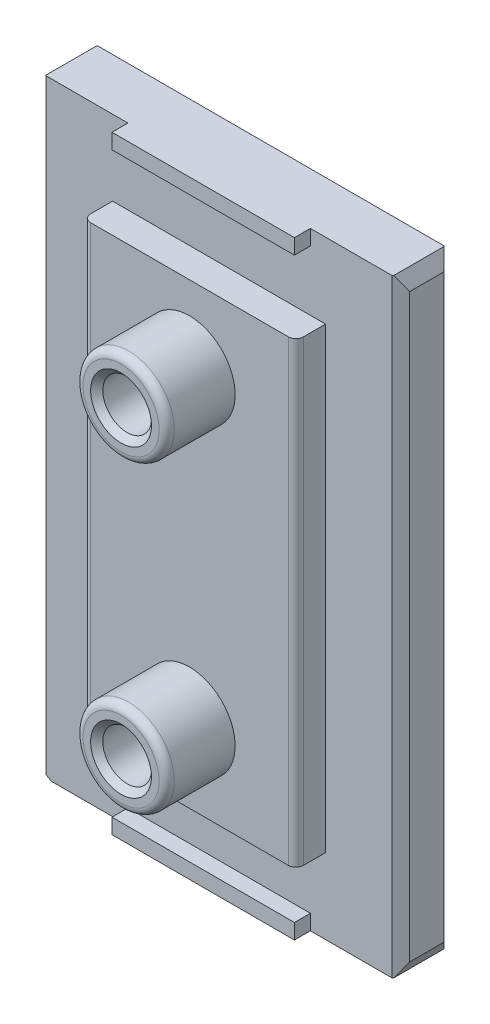
SolidWorks part; units mm, degrees
ref_plane "Plan de face" through (0, 0, 0) normal (0, 0, 1) x (1, 0, 0)
ref_plane "Plan de dessus" through (0, 0, 0) normal (0, 1, 0) x (1, 0, 0)
ref_plane "Plan de droite" through (0, 0, 0) normal (1, 0, 0) x (0, 0, -1)
ref_plane "Plan1" through (0, 0, 7.55) normal (0, 0, 1) x (1, 0, 0)
sketch "Esquisse1" plane through (0, 0, 7.55) normal (0, 0, 1) x (1, 0, 0)
  line L0 (11.95, 20) -> (-11.95, 20)
  line L1 (-11.95, 20) -> (-11.95, -20)
  line L2 (-11.95, -20) -> (11.95, -20)
  line L3 (11.95, -20) -> (11.95, 20)
extrude "Boss.-Extru.1" add sketch "Esquisse1" against normal blind 3.4
ref_plane "Plan2" through (0, 15, 0) normal (0, 1, 0) x (1, 0, 0)
sketch "Esquisse2" plane through (0, 15, 0) normal (0, 1, 0) x (1, 0, 0)
  line L0 (6.995, -7.4) -> (6.995, -7.55)
  line L1 (6.995, -7.55) -> (7, -7.55)
  line L2 (7, -7.55) -> (7, -7.3107)
  arc A0 (7, -7.3107) -> (6.995, -7.4) centre (7.795, -7.4) ccw
extrude "Enlèv. mat.-Extru.1" cut sketch "Esquisse2" against normal blind 30
sketch "Esquisse3" plane through (0, 0, 7.55) normal (0, 0, 1) x (1, 0, 0)
  line L0 (-7.005, 15.05) -> (6.995, 15.05)
  line L1 (6.995, 15.05) -> (6.995, -15.05)
  line L2 (6.995, -15.05) -> (-7.005, -15.05)
  line L3 (-7.005, -15.05) -> (-7.005, 15.05)
extrude "Boss.-Extru.2" add sketch "Esquisse3" along normal blind 1.95
sketch "Esquisse4" plane through (0, 0, 4.15) normal (0, 0, -1) x (-1, 0, 0)
  line L0 (5.2, 15) -> (-5.2, 15)
  line L1 (-5.2, 15) -> (-5.2, -15)
  line L2 (-5.2, -15) -> (5.2, -15)
  line L3 (5.2, -15) -> (5.2, 15)
extrude "Enlèv. mat.-Extru.2" cut sketch "Esquisse4" against normal blind 1.55
ref_plane "Plan3" through (0, 0, 4.15) normal (0, 0, -1) x (-1, 0, 0)
ref_plane "Plan4" through (0, 0, 5.1) normal (0, 0, 1) x (1, 0, 0)
sketch "Esquisse6" plane through (0, 0, 5.1) normal (0, 0, 1) x (1, 0, 0)
  line L0 (5.2, -15) -> (-5.2, -15)
  line L1 (-5.2, -15) -> (-5.2, -16.75)
  line L2 (-5.2, -16.75) -> (5.2, -16.75)
  line L3 (5.2, -16.75) -> (5.2, -15)
extrude "Enlèv. mat.-Extru.3" cut sketch "Esquisse6" against normal up to surface up to plane "Plan3"
sketch "Esquisse8" plane through (0, 0, 5.1) normal (0, 0, 1) x (1, 0, 0)
  line L0 (-5.2, 15) -> (5.2, 15)
  line L1 (5.2, 15) -> (5.2, 16.75)
  line L2 (5.2, 16.75) -> (-5.2, 16.75)
  line L3 (-5.2, 16.75) -> (-5.2, 15)
extrude "Enlèv. mat.-Extru.4" cut sketch "Esquisse8" against normal up to surface up to plane "Plan3"
sketch "Esquisse9" plane through (5.2, 0, 0) normal (-1, 0, 0) x (0, 0, 1)
  line L0 (5.7, -15) -> (5.7, 15)
  line L1 (5.7, 15) -> (5.1, 15)
  line L2 (5.1, 15) -> (5.1, -15)
  line L3 (5.1, -15) -> (5.7, -15)
extrude "Enlèv. mat.-Extru.5" cut sketch "Esquisse9" against normal blind 1.8
sketch "Esquisse10" plane through (-5.2, 0, 0) normal (1, 0, 0) x (0, 0, -1)
  line L0 (-5.7, 15) -> (-5.7, -15)
  line L1 (-5.7, -15) -> (-5.1, -15)
  line L2 (-5.1, -15) -> (-5.1, 15)
  line L3 (-5.1, 15) -> (-5.7, 15)
extrude "Enlèv. mat.-Extru.6" cut sketch "Esquisse10" against normal blind 1.8
sketch "Esquisse11" plane through (0, 0, 7.55) normal (0, 0, 1) x (1, 0, 0)
  line L0 (-6, -20) -> (-6, -19)
  line L1 (-6, -19) -> (6, -19)
  line L2 (6, -19) -> (6, -20)
  line L3 (6, -20) -> (-6, -20)
extrude "Boss.-Extru.3" add sketch "Esquisse11" along normal blind 1.05
sketch "Esquisse12" plane through (0, 0, 7.55) normal (0, 0, 1) x (1, 0, 0)
  line L0 (-6, 19) -> (-6, 20)
  line L1 (-6, 20) -> (6, 20)
  line L2 (6, 20) -> (6, 19)
  line L3 (6, 19) -> (-6, 19)
extrude "Boss.-Extru.4" add sketch "Esquisse12" along normal blind 1.05
ref_plane "Plan5" through (0, 10, 0) normal (0, -1, 0) x (1, 0, 0)
sketch "Esquisse13" plane through (0, 10, 0) normal (0, -1, 0) x (1, 0, 0)
  line L0 (3, 14) -> (0, 14)
  line L1 (0, 14) -> (0, 9.5)
  line L2 (0, 9.5) -> (3, 9.5)
  line L3 (3, 9.5) -> (3, 14)
  line L4 (0, 14) -> (0, 9.5) construction
revolve "Révolution1" add sketch "Esquisse13" angle 360 about L4
ref_plane "Plan6" through (0, -10, 0) normal (0, -1, 0) x (1, 0, 0)
sketch "Esquisse14" plane through (0, -10, 0) normal (0, -1, 0) x (1, 0, 0)
  line L0 (3, 14) -> (0, 14)
  line L1 (0, 14) -> (0, 9.5)
  line L2 (0, 9.5) -> (3, 9.5)
  line L3 (3, 9.5) -> (3, 14)
  line L4 (0, 14) -> (0, 9.5) construction
revolve "Révolution2" add sketch "Esquisse14" angle 360 about L4
hole_wizard "Chambrage pour vis à tête hexagonale M31" positions "Esquisse16" profile "Esquisse15" counterbore size "M3" standard "Ansi Metric"
sketch "Esquisse16" plane through (0, 0, 5.7) normal (0, 0, -1) x (-1, 0, 0)
  point P0 (0, -10)
  point P1 (0, 10)
sketch "Esquisse15" plane through (0, -10, 5.7) normal (1, 0, 0) x (0, 1, 0)
  line L0 (0, 0) -> (0, 8.3)
  line L1 (0, 8.3) -> (1.6, 8.3)
  line L3 (1.6, 8.3) -> (1.6, 2.3)
  line L4 (1.6, 2.3) -> (4, 2.3)
  line L5 (4, 2.3) -> (4, 0)
  line L7 (4, 0) -> (0, 0)
  line L11 (0, -6.35) -> (0, 107.95) construction
  dimension "Diamètre du perçage jusqu'au prochain" = 3.2
  dimension "Profondeur du perçage jusqu'au prochain" = 8.3
  dimension "Diamètre du chambrage" = 8
  dimension "Profondeur du chambrage" = 2.3
chamfer "Chanfrein1" distance 0.9133 angle 29.985 1 edges at (11.95, 20, 5.85)
chamfer "Chanfrein2" distance 0.527 angle 60.015 3 edges at (-11.95, -20, 5.85) (-11.95, 20, 5.85) (11.95, -20, 5.85)
chamfer "Chanfrein3" distance 0.577 angle 45 4 edges at (-11.95, -0.1932, 4.15) (-11.95, -0.1932, 7.55) (11.95, 0, 4.15) (11.95, 0, 7.55)
chamfer "Chanfrein4" distance 0.4 angle 45 4 edges at (-1.6, -10, 8) (-1.6, 10, 14) (-1.6, 10, 8) (-1.6, -10, 14)
fillet "Congé1" radius 0.5 4 edges at (6.995, 0, 9.5) (-3, 10, 14) (-3, -10, 14) (-7.005, 0, 9.5)
